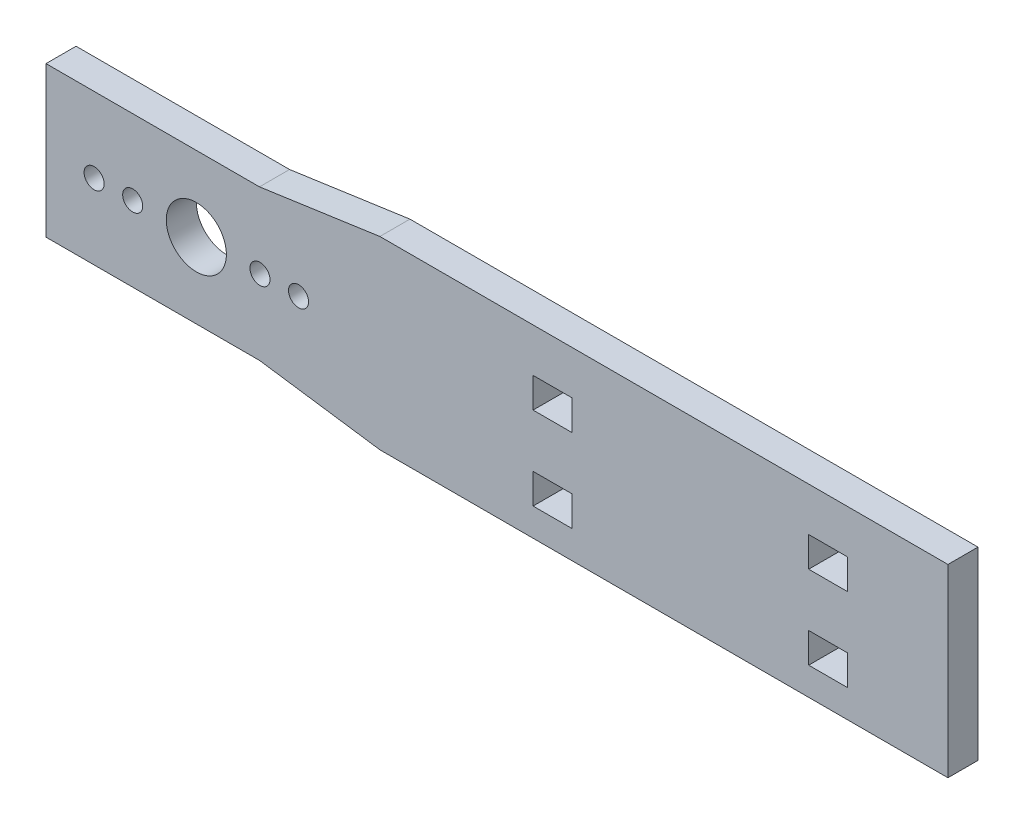
SolidWorks part; units mm, degrees
ref_plane "Front Plane" through (0, 0, 0) normal (0, 0, 1) x (1, 0, 0)
ref_plane "Top Plane" through (0, 0, 0) normal (0, 1, 0) x (1, 0, 0)
ref_plane "Right Plane" through (0, 0, 0) normal (1, 0, 0) x (0, 0, -1)
sketch "Model" plane through (0, 0, 0) normal (0, 0, 1) x (1, 0, 0)
  line L207 (-325.1011, 303.6325) -> (-325.1011, 281.9366)
  line L210 (-398.2841, 298.0765) -> (-364.3981, 303.6325)
  line L211 (-398.2841, 287.6841) -> (-364.0012, 281.9366)
  line L212 (-328.3518, 297.4919) -> (-328.3518, 294.4919)
  line L213 (-328.3518, 294.4919) -> (-333.3048, 294.4919)
  line L214 (-333.3048, 294.4919) -> (-333.3048, 297.4919)
  line L215 (-333.3048, 297.4919) -> (-328.3518, 297.4919)
  line L216 (-356.7454, 297.4919) -> (-356.7454, 294.4919)
  line L217 (-356.7454, 294.4919) -> (-361.6984, 294.4919)
  line L218 (-361.6984, 294.4919) -> (-361.6984, 297.4919)
  line L219 (-361.6984, 297.4919) -> (-356.7454, 297.4919)
  line L220 (-328.3518, 289.1977) -> (-328.3518, 286.1977)
  line L221 (-328.3518, 286.1977) -> (-333.3048, 286.1977)
  line L222 (-333.3048, 286.1977) -> (-333.3048, 289.1977)
  line L223 (-333.3048, 289.1977) -> (-328.3518, 289.1977)
  line L224 (-356.7454, 289.1977) -> (-356.7454, 286.1977)
  line L225 (-356.7454, 286.1977) -> (-361.6984, 286.1977)
  line L226 (-361.6984, 286.1977) -> (-361.6984, 289.1977)
  line L227 (-361.6984, 289.1977) -> (-356.7454, 289.1977)
  line L246 (-399.3267, 292.8803) -> (-399.5986, 292.5257)
  line L247 (-399.5986, 292.5257) -> (-399.496, 292.0923)
  line L248 (-399.496, 292.0923) -> (-399.8901, 291.8778)
  line L249 (-399.8901, 291.8778) -> (-399.9743, 291.4406)
  line L250 (-399.9743, 291.4406) -> (-400.4225, 291.4033)
  line L251 (-400.4225, 291.4033) -> (-400.6792, 291.0378)
  line L252 (-400.6792, 291.0378) -> (-401.1039, 291.1841)
  line L253 (-401.1039, 291.1841) -> (-401.4886, 290.9535)
  line L254 (-401.4886, 290.9535) -> (-401.8166, 291.2582)
  line L255 (-401.8166, 291.2582) -> (-402.2627, 291.2025)
  line L256 (-402.2627, 291.2025) -> (-402.437, 291.6128)
  line L257 (-402.437, 291.6128) -> (-402.8676, 291.7416)
  line L258 (-402.8676, 291.7416) -> (-402.8582, 292.1866)
  line L259 (-402.8582, 292.1866) -> (-403.1986, 292.4775)
  line L260 (-403.1986, 292.4775) -> (-403.0072, 292.8803)
  line L261 (-403.0072, 292.8803) -> (-403.1986, 293.2831)
  line L262 (-403.1986, 293.2831) -> (-402.8582, 293.574)
  line L263 (-402.8582, 293.574) -> (-402.8676, 294.019)
  line L264 (-402.8676, 294.019) -> (-402.437, 294.1478)
  line L265 (-402.437, 294.1478) -> (-402.2627, 294.5581)
  line L266 (-402.2627, 294.5581) -> (-401.8166, 294.5024)
  line L267 (-401.8166, 294.5024) -> (-401.4886, 294.8071)
  line L268 (-401.4886, 294.8071) -> (-401.1039, 294.5765)
  line L269 (-401.1039, 294.5765) -> (-400.6792, 294.7228)
  line L270 (-400.6792, 294.7228) -> (-400.4225, 294.3573)
  line L271 (-400.4225, 294.3573) -> (-399.9743, 294.32)
  line L272 (-399.9743, 294.32) -> (-399.8901, 293.8828)
  line L273 (-399.8901, 293.8828) -> (-399.496, 293.6683)
  line L274 (-399.496, 293.6683) -> (-399.5986, 293.2349)
  line L275 (-399.5986, 293.2349) -> (-399.3267, 292.8803)
  spline S328 degree 3 poles (-398.2841, 298.0765) (-399.1963, 298.6031) (-400.2309, 298.8803) (-401.2841, 298.8803) knots 0 0 0 0 0.2 0.2 0.2 0.2
  spline S329 degree 3 poles (-401.2841, 298.8803) (-404.5978, 298.8803) (-407.284, 296.1941) (-407.284, 292.8803) knots 0.2 0.2 0.2 0.2 0.4 0.4 0.4 0.4
  spline S330 degree 3 poles (-407.284, 292.8803) (-407.284, 289.5665) (-404.5978, 286.8803) (-401.2841, 286.8803) knots 0.4 0.4 0.4 0.4 0.6 0.6 0.6 0.6
  spline S331 degree 3 poles (-401.2841, 286.8803) (-400.2309, 286.8803) (-399.1963, 287.1575) (-398.2841, 287.6841) knots 0.6 0.6 0.6 0.6 1 1 1 1
sketch "Sketch1" plane through (0, 0, 0) normal (0, 0, 1) x (1, 0, 0)
  line L0 (-398.2841, 298.0765) -> (-386.2712, 299.7943)
  line L1 (-386.2712, 299.7943) -> (-329.5874, 299.7943)
  line L2 (-329.5874, 299.7943) -> (-329.5874, 281.3587)
  line L3 (-329.5874, 281.3587) -> (-386.2712, 281.3587)
  line L4 (-386.2712, 281.3587) -> (-398.2841, 283.0765)
  line L5 (-419.5874, 290.5765) -> (-329.5874, 290.5765) construction
  line L6 (-370.9846, 295.4351) -> (-367.1046, 295.4351)
  line L7 (-370.9846, 295.4351) -> (-370.9846, 292.4351)
  line L8 (-370.9846, 292.4351) -> (-367.1046, 292.4351)
  line L9 (-367.1046, 295.4351) -> (-367.1046, 292.4351)
  line L10 (-370.9846, 287.1409) -> (-367.1046, 287.1409)
  line L11 (-370.9846, 287.1409) -> (-370.9846, 284.1409)
  line L12 (-370.9846, 284.1409) -> (-367.1046, 284.1409)
  line L13 (-367.1046, 287.1409) -> (-367.1046, 284.1409)
  line L14 (-343.4826, 295.4351) -> (-339.6026, 295.4351)
  line L15 (-343.4826, 295.4351) -> (-343.4826, 292.4351)
  line L16 (-343.4826, 292.4351) -> (-339.6026, 292.4351)
  line L17 (-339.6026, 295.4351) -> (-339.6026, 292.4351)
  line L18 (-343.4826, 287.1409) -> (-339.6026, 287.1409)
  line L19 (-343.4826, 287.1409) -> (-343.4826, 284.1409)
  line L20 (-343.4826, 284.1409) -> (-339.6026, 284.1409)
  line L21 (-339.6026, 287.1409) -> (-339.6026, 284.1409)
  line L23 (-398.2841, 298.0765) -> (-419.5874, 298.0765)
  line L25 (-398.2841, 283.0765) -> (-419.5874, 283.0765)
  line L26 (-419.5874, 298.0765) -> (-419.5874, 283.0765)
  circle A1 centre (-404.5861, 290.5765) radius 3
  dimension "D3" = 90
  dimension "D1" = 10.0152
  dimension "D2" = 15
  dimension "D4" = 10.0152
  dimension "D5" = 23.622
  dimension "D6" = 23.622
  dimension "D8" = 3.88
  dimension "D9" = 3
extrude "Boss-Extrude1" add sketch "Sketch1" along normal blind 3
sketch "Sketch2" plane through (0, 0, 3) normal (0, 0, 1) x (1, 0, 0)
  circle A0 centre (-414.7861, 290.5765) radius 1.0009
  circle A1 centre (-410.9361, 290.5765) radius 1.0009
  circle A2 centre (-398.2361, 290.5765) radius 1.0009
  circle A3 centre (-394.3861, 290.5765) radius 1.0009
  dimension "D1" = 2.0018
  dimension "D2" = 2.0018
  dimension "D3" = 2.0018
  dimension "D4" = 2.0018
extrude "Cut-Extrude1" cut sketch "Sketch2" against normal through all
equation "\"selftap\"=2.0018"
equation "\"D1@Sketch2\"=\"selftap\""
equation "\"D2@Sketch2\"=\"selftap\""
equation "\"D4@Sketch2\"=\"selftap\""
equation "\"D3@Sketch2\"=\"selftap\""
